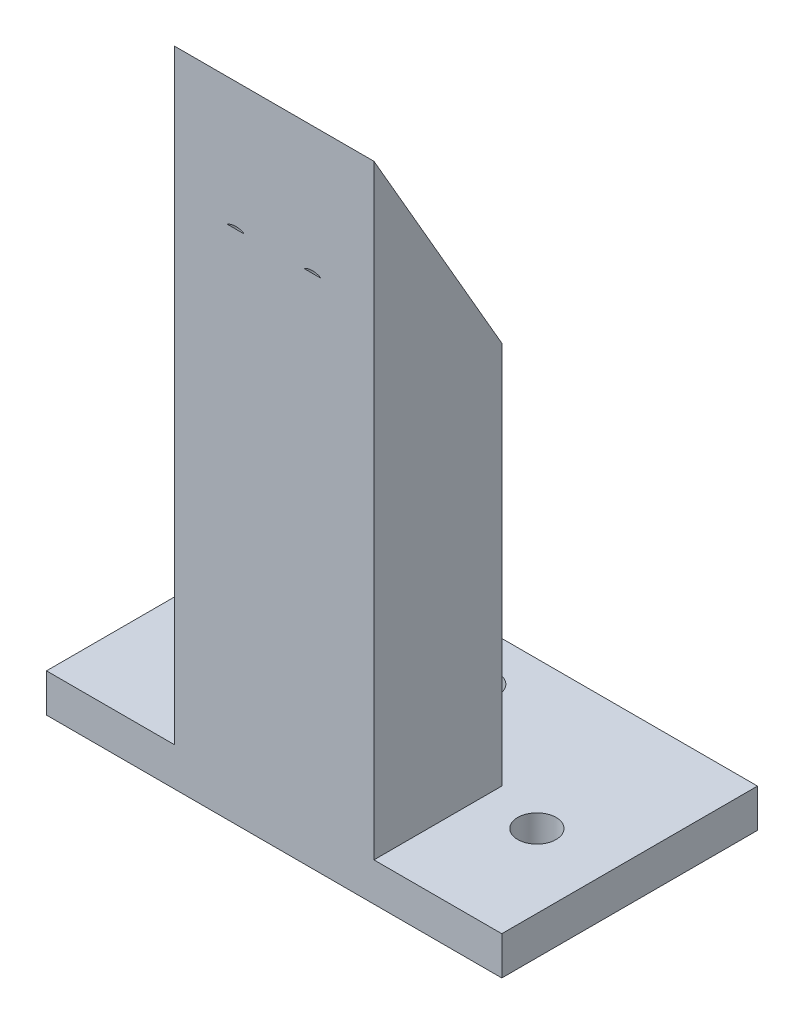
SolidWorks part; units mm, degrees
ref_plane "Front Plane" through (0, 0, 0) normal (0, 0, 1) x (1, 0, 0)
ref_plane "Top Plane" through (0, 0, 0) normal (0, 1, 0) x (1, 0, 0)
ref_plane "Right Plane" through (0, 0, 0) normal (1, 0, 0) x (0, 0, -1)
sketch "Sketch1" plane through (0, 0, 0) normal (0, 1, 0) x (1, 0, 0)
  line L0 (-8.4368, 20.25) -> (-8.4368, 0.25) construction
  line L1 (-26.2418, 20.25) -> (9.3682, 20.25)
  line L2 (-26.2418, 20.25) -> (-26.2418, 0.25)
  line L3 (-26.2418, 0.25) -> (9.3682, 0.25)
  line L4 (9.3682, 20.25) -> (9.3682, 0.25)
  line L5 (-26.2418, 0.25) -> (9.3682, 0.25)
  line L9 (-23.1318, 20.25) -> (6.2583, 20.25) construction
  line L10 (9.3682, 0.25) -> (-26.2418, 0.25)
  point P10 (-8.4368, 0.25)
  dimension "D1" = 20
  dimension "D2" = 35.61
extrude "Boss-Extrude1" add sketch "Sketch1" along normal blind 3
ref_plane "Plane2" through (-8.4368, 0, 0) normal (1, 0, 0) x (0, 0, -1)
sketch "Sketch3" plane through (0, 0, 0) normal (0, -1, 0) x (1, 0, 0)
  circle A0 centre (-20.4847, -8.75) radius 1.5
  circle A1 centre (-8.4349, -16.25) radius 1.5
  circle A2 centre (3.6149, -8.75) radius 1.5
  dimension "D1" = 3
extrude "Cut-Extrude1" cut sketch "Sketch3" against normal blind 5
sketch "Sketch7" plane through (0, 3, 0) normal (0, 1, 0) x (1, 0, 0)
  line L0 (-26.2418, 20.25) -> (-26.2418, 0.25) construction
  line L1 (-16.2418, 10.25) -> (-0.6318, 10.25)
  line L2 (-16.2418, 10.25) -> (-16.2418, 0.25)
  line L3 (-16.2418, 0.25) -> (-0.6318, 0.25)
  line L4 (-0.6318, 10.25) -> (-0.6318, 0.25)
  line L5 (9.3682, 20.25) -> (9.3682, 0.25) construction
  dimension "D1" = 10
  dimension "D2" = 10
  dimension "D4" = 10
extrude "Boss-Extrude4" add sketch "Sketch7" along normal blind 30
sketch "Sketch8" plane through (-16.2418, 0, 0) normal (-1, 0, 0) x (0, 0, 1)
  line L0 (-10.25, 33) -> (-0.25, 50.3205)
  line L1 (-0.25, 33) -> (-0.25, 50.3205)
  line L2 (-10.25, 33) -> (-0.25, 33) construction
  line L3 (-10.25, 33) -> (-0.25, 33)
  dimension "D1" = 60
extrude "Boss-Extrude5" add sketch "Sketch8" against normal up to surface (15.61 mm away) up to face at (-0.6318, 18, -5.25)
sketch "Sketch9" plane through (0, 12.6884, -21.9769) normal (0, 0.5, -0.866) x (1, 0, 0)
  line L0 (-16.2418, -33.4538) -> (-0.6318, -33.4538) construction
  line L1 (-16.2418, -43.4538) -> (-16.2418, -23.4538) construction
  line L2 (-0.6318, -23.4538) -> (-0.6318, -43.4538) construction
  line L3 (-8.4368, -23.4538) -> (-8.4368, -43.4538) construction
  line L4 (-0.6318, -23.4538) -> (-16.2418, -23.4538) construction
  line L5 (-0.6318, -43.4538) -> (-16.2418, -43.4538) construction
  circle A0 centre (-11.4368, -33.4538) radius 1.5
  circle A1 centre (-5.4368, -33.4538) radius 1.5
  dimension "D1" = 3
  dimension "D2" = 3
  dimension "D3" = 6
  dimension "D4" = 3
extrude "Cut-Extrude2" cut sketch "Sketch9" against normal blind 5
